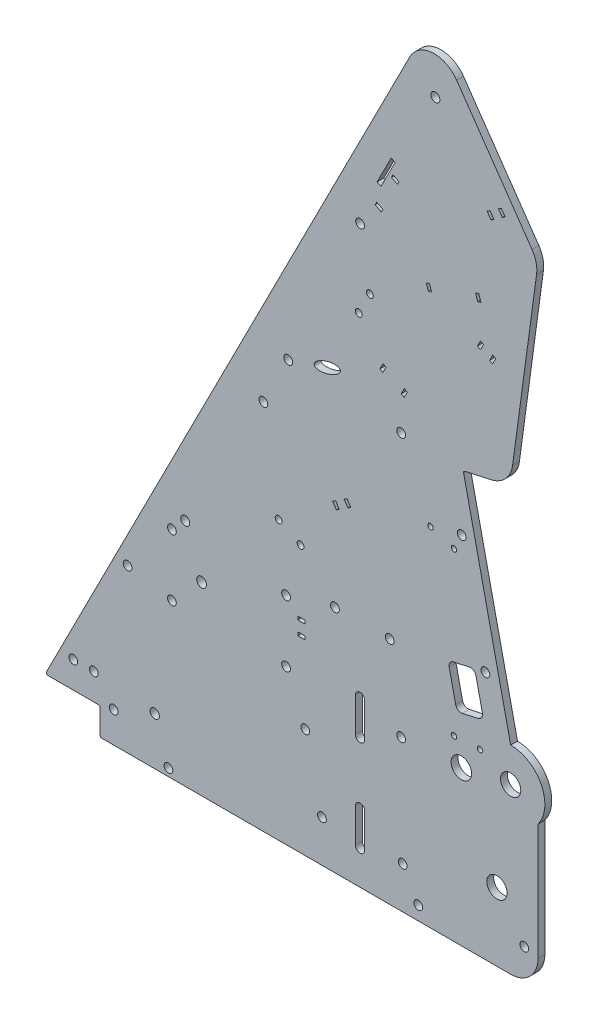
SolidWorks part; units mm, degrees
other "Markup1"
sketch "Sketch5"
ref_plane "Front Plane" through (0, 0, 0) normal (0, 0, 1) x (1, 0, 0)
ref_plane "Top Plane" through (0, 0, 0) normal (0, 1, 0) x (1, 0, 0)
ref_plane "Right Plane" through (0, 0, 0) normal (1, 0, 0) x (0, 0, -1)
sketch "Sketch1" plane through (0, 0, 0) normal (0, 0, 1) x (1, 0, 0)
  line L1 (228.6, -12.7) -> (228.6, 53.975)
  line L2 (178.7547, 351.4131) -> (0, 0)
  line L3 (228.6, 279.4) -> (178.7547, 351.4131)
  line L5 (0, 0) -> (25.4, 0)
  line L6 (25.4, 0) -> (25.4, -12.7)
  line L7 (25.4, -12.7) -> (228.6, -12.7)
  line L9 (215.9, 79.375) -> (193.9097, 178.5667)
  line L10 (193.9097, 178.5667) -> (215.6079, 183.377)
  line L11 (215.6079, 183.377) -> (228.6, 279.4)
  arc A0 (228.6, 53.975) -> (215.9, 79.375) centre (215.9, 63.5) ccw
  dimension "D7" = 12.7
  dimension "D8" = 76.2
  dimension "D10" = 31.75
  dimension "D2" = 292.1
  dimension "D3" = 25.4
  dimension "D4" = 215.9
  dimension "D5" = 394.2644
  dimension "D6" = 203.2
  dimension "D9" = 63.039
  dimension "D11" = 101.6
  dimension "D12" = 12.5
  dimension "D13" = 22.225
extrude "Boss-Extrude1" add sketch "Sketch1" along normal blind 3.175
sketch "Sketch2" plane through (0, 0, 3.175) normal (0, 0, 1) x (1, 0, 0)
  line L0 (178.7547, 351.4131) -> (0, 0) construction
  line L1 (25.4, -12.7) -> (228.6, -12.7) construction
  line L2 (215.9, 79.375) -> (193.9097, 178.5667) construction
  line L3 (193.9097, 178.5667) -> (215.6079, 183.377) construction
  line L4 (215.9, 79.375) -> (193.9097, 178.5667) construction
  line L5 (64.9432, 94.0578) -> (72.5445, 73.1732) construction
  line L6 (64.9432, 94.0578) -> (103.3734, 94.0578) construction
  line L10 (228.6, -12.7) -> (228.6, 53.975) construction
  circle A0 centre (64.9432, 94.0578) radius 2.0955
  circle A1 centre (180.975, 322.1643) radius 2.0955
  circle A2 centre (72.5445, 73.1732) radius 2.286
  circle A3 centre (193.2078, 152.3944) radius 2.032
  circle A4 centre (215.9, 63.5) radius 4.699
  circle A7 centre (173.0375, -6.35) radius 2.032
  circle A8 centre (204.203, 102.7985) radius 2.032
  circle A26 centre (209.55, 19.05) radius 4.699
  arc A30 (228.6, 53.975) -> (215.9, 79.375) centre (215.9, 63.5) ccw construction
  circle A31 centre (165.1, 179.3875) radius 2.032
  circle A35 centre (111.724, 87.4607) radius 2.032
  circle A36 centre (111.724, 58.8857) radius 2.032
  circle A37 centre (58.765, 58.8857) radius 2.032
  circle A38 centre (58.765, 87.4607) radius 2.032
  circle A39 centre (111.724, 58.8857) radius 1.905 construction
  circle A42 centre (111.724, 87.4607) radius 1.905 construction
  circle A43 centre (58.765, 58.8857) radius 1.905 construction
  circle A44 centre (58.765, 87.4607) radius 1.905 construction
  dimension "D3" = 4.191
  dimension "D5" = 4.191
  dimension "D9" = 4.572
  dimension "D20" = 9.398
  dimension "D23" = 9.398
  dimension "D18" = 4.064
  dimension "D26" = 4.064
  dimension "D14" = 4.064
  dimension "D10" = 4.064
  dimension "D2" = 15.24
  dimension "D6" = 15.24
  dimension "D7" = 22.225
  dimension "D21" = 44.45
  dimension "D22" = 6.35
  dimension "D19" = 160.3375
  dimension "D24" = 44.45
  dimension "D25" = 6.35
  dimension "D27" = 25.4
  dimension "D28" = 50.8
  dimension "D29" = 6.35
  dimension "D17" = 6.35
  dimension "D33" = 55.5625
  dimension "D15" = 114.3
  dimension "D4" = 180.975
  dimension "D8" = 70
extrude "Cut-Extrude1" cut sketch "Sketch2" against normal through all
sketch "Sketch7" plane through (0, 0, 3.175) normal (0, 0, 1) x (1, 0, 0)
  line L0 (146.05, 3.175) -> (146.05, 19.05) construction
  line L1 (143.891, 3.175) -> (143.891, 19.05)
  line L2 (148.209, 3.175) -> (148.209, 19.05)
  line L3 (146.05, 47.625) -> (146.05, 63.5) construction
  line L4 (143.891, 47.625) -> (143.891, 63.5)
  line L5 (148.209, 47.625) -> (148.209, 63.5)
  line L6 (25.4, -12.7) -> (228.6, -12.7) construction
  line L12 (228.6, -12.7) -> (228.6, 53.975) construction
  line L13 (25.4, -12.7) -> (228.6, -12.7) construction
  arc A0 (143.891, 3.175) -> (148.209, 3.175) centre (146.05, 3.175) ccw
  arc A1 (148.209, 19.05) -> (143.891, 19.05) centre (146.05, 19.05) ccw
  arc A2 (143.891, 47.625) -> (148.209, 47.625) centre (146.05, 47.625) ccw
  arc A3 (148.209, 63.5) -> (143.891, 63.5) centre (146.05, 63.5) ccw
  circle A8 centre (50.8, 9.525) radius 2.159
  point P2 (146.05, 11.1125)
  point P9 (146.05, 55.5625)
  dimension "D1" = 4.318
  dimension "D5" = 4.318
  dimension "D2" = 15.875
  dimension "D3" = 15.875
  dimension "D4" = 44.45
  dimension "D6" = 95.25
  dimension "D7" = 82.55
  dimension "D8" = 15.875
  dimension "D9" = 22.225
extrude "Cut-Extrude2" cut sketch "Sketch7" against normal through all
sketch "Sketch10" plane through (0, 0, 3.175) normal (0, 0, 1) x (1, 0, 0)
  circle A0 centre (120.65, 38.1) radius 2.032
  circle A1 centre (165.1, 57.15) radius 2.032
  circle A2 centre (13.0465, 12.3347) radius 2.032
  circle A3 centre (22.5715, 12.3347) radius 2.032
  circle A4 centre (38.2114, 62.6398) radius 2.032
  dimension "D1" = 4.064
  dimension "D3" = 38.1
  dimension "D2" = 120.65
  dimension "D4" = 63.5
  dimension "D5" = 69.85
extrude "Cut-Extrude3" cut sketch "Sketch10" against normal up to next
fillet "Fillet1" radius 12.7 4 edges at (228.6, -12.7, 1.5875) (178.7547, 351.4131, 1.5875) (215.6079, 183.377, 1.5875) (228.6, 279.4, 1.5875)
fillet "Fillet2" radius 0.7937 4 edges at (25.4, -12.7, 1.5875) (25.4, 0, 1.5875) (193.9097, 178.5667, 1.5875) (0, 0, 1.5875)
sketch "Sketch12" plane through (0, 0, 3.175) normal (0, 0, 1) x (1, 0, 0)
  circle A0 centre (31.75, 1.5875) radius 2.032
  circle A1 centre (173.0375, -6.35) radius 2.032
  circle A2 centre (222.25, 1.5875) radius 2.032
  circle A3 centre (57.15, -9.2075) radius 2.032
  circle A4 centre (57.15, -9.2075) radius 2.286 construction
  dimension "D1" = 4.064
  dimension "D2" = 4.064
extrude "Cut-Extrude5" cut sketch "Sketch12" against normal through all
sketch "Sketch13" plane through (0, 0, 3.175) normal (0, 0, 1) x (1, 0, 0)
  line L1 (228.6, 0) -> (228.6, 53.975) construction
  line L2 (1.2943, 0) -> (24.6062, 0) construction
  line L3 (26.1937, -12.7) -> (215.9, -12.7) construction
  line L8 (178.2697, 245.9923) -> (176.7582, 245.5069)
  line L9 (179.2404, 242.9693) -> (178.2697, 245.9923)
  line L10 (177.7289, 242.4839) -> (179.2404, 242.9693)
  line L11 (176.7582, 245.5069) -> (177.7289, 242.4839)
  line L12 (178.2697, 245.9923) -> (176.7582, 245.5069)
  line L13 (179.2404, 242.9693) -> (178.2697, 245.9923)
  line L14 (177.7289, 242.4839) -> (179.2404, 242.9693)
  line L15 (176.7582, 245.5069) -> (177.7289, 242.4839)
  line L16 (153.9381, 274.6148) -> (160.5022, 287.5193)
  line L17 (200.6096, 249.8308) -> (202.1211, 250.3161)
  line L18 (199.639, 252.8538) -> (200.6096, 249.8308)
  line L19 (201.1505, 253.3391) -> (199.639, 252.8538)
  line L20 (202.1211, 250.3161) -> (201.1505, 253.3391)
  line L21 (200.6096, 249.8308) -> (202.1211, 250.3161)
  line L22 (199.639, 252.8538) -> (200.6096, 249.8308)
  line L23 (201.1505, 253.3391) -> (199.639, 252.8538)
  line L24 (202.1211, 250.3161) -> (201.1505, 253.3391)
  line L25 (153.9381, 274.6148) -> (155.7207, 273.708)
  line L26 (160.5905, 279.7801) -> (163.4204, 278.3406)
  line L27 (161.3102, 281.1951) -> (160.5905, 279.7801)
  line L28 (164.1402, 279.7556) -> (161.3102, 281.1951)
  line L29 (163.4204, 278.3406) -> (164.1402, 279.7556)
  line L30 (160.5905, 279.7801) -> (163.4204, 278.3406)
  line L31 (161.3102, 281.1951) -> (160.5905, 279.7801)
  line L32 (164.1402, 279.7556) -> (161.3102, 281.1951)
  line L33 (163.4204, 278.3406) -> (164.1402, 279.7556)
  line L34 (160.5022, 287.5193) -> (162.2849, 286.6125)
  line L35 (155.7207, 273.708) -> (162.2849, 286.6125)
  line L36 (153.7897, 266.4104) -> (153.0699, 264.9954)
  line L37 (156.6196, 264.9709) -> (153.7897, 266.4104)
  line L38 (155.8998, 263.5559) -> (156.6196, 264.9709)
  line L39 (153.0699, 264.9954) -> (155.8998, 263.5559)
  line L40 (153.7897, 266.4104) -> (153.0699, 264.9954)
  line L41 (156.6196, 264.9709) -> (153.7897, 266.4104)
  line L42 (155.8998, 263.5559) -> (156.6196, 264.9709)
  line L43 (153.0699, 264.9954) -> (155.8998, 263.5559)
  line L110 (153.9925, 274.7218) -> (157.3929, 281.4066) construction
  line L111 (155.7751, 273.815) -> (159.1755, 280.4999) construction
  line L122 (203.3303, 234.0299) -> (201.9154, 234.7497)
  line L123 (201.8908, 231.2) -> (203.3303, 234.0299)
  line L124 (200.4759, 231.9198) -> (201.8908, 231.2)
  line L125 (201.9154, 234.7497) -> (200.4759, 231.9198)
  line L126 (203.3303, 234.0299) -> (201.9154, 234.7497)
  line L127 (201.8908, 231.2) -> (203.3303, 234.0299)
  line L128 (200.4759, 231.9198) -> (201.8908, 231.2)
  line L129 (201.9154, 234.7497) -> (200.4759, 231.9198)
  line L130 (206.1357, 229.0407) -> (207.5507, 228.321)
  line L131 (207.5752, 231.8707) -> (206.1357, 229.0407)
  line L132 (208.9902, 231.1509) -> (207.5752, 231.8707)
  line L133 (207.5507, 228.321) -> (208.9902, 231.1509)
  line L134 (206.1357, 229.0407) -> (207.5507, 228.321)
  line L135 (207.5752, 231.8707) -> (206.1357, 229.0407)
  line L136 (208.9902, 231.1509) -> (207.5752, 231.8707)
  line L137 (207.5507, 228.321) -> (208.9902, 231.1509)
  line L138 (211.5405, 292.889) -> (210.2352, 291.9855)
  line L139 (213.3475, 290.2784) -> (211.5405, 292.889)
  line L140 (212.0422, 289.3749) -> (213.3475, 290.2784)
  line L141 (210.2352, 291.9855) -> (212.0422, 289.3749)
  line L142 (211.5405, 292.889) -> (210.2352, 291.9855)
  line L143 (213.3475, 290.2784) -> (211.5405, 292.889)
  line L144 (212.0422, 289.3749) -> (213.3475, 290.2784)
  line L145 (210.2352, 291.9855) -> (212.0422, 289.3749)
  line L146 (206.3193, 289.275) -> (205.014, 288.3715)
  line L147 (208.1263, 286.6644) -> (206.3193, 289.275)
  line L148 (206.821, 285.7609) -> (208.1263, 286.6644)
  line L149 (205.014, 288.3715) -> (206.821, 285.7609)
  line L150 (206.3193, 289.275) -> (205.014, 288.3715)
  line L151 (208.1263, 286.6644) -> (206.3193, 289.275)
  line L152 (206.821, 285.7609) -> (208.1263, 286.6644)
  line L153 (205.014, 288.3715) -> (206.821, 285.7609)
  line L184 (133.3504, 136.102) -> (135.0815, 133.4404)
  line L185 (133.3504, 136.102) -> (134.6812, 136.9675)
  line L186 (135.0815, 133.4404) -> (136.4123, 134.3059)
  line L187 (155.2281, 200.1197) -> (156.643, 199.3999)
  line L188 (156.6676, 202.9496) -> (155.2281, 200.1197)
  line L189 (158.0826, 202.2298) -> (156.6676, 202.9496)
  line L190 (156.643, 199.3999) -> (158.0826, 202.2298)
  line L191 (155.2281, 200.1197) -> (156.643, 199.3999)
  line L192 (156.6676, 202.9496) -> (155.2281, 200.1197)
  line L193 (158.0826, 202.2298) -> (156.6676, 202.9496)
  line L194 (156.643, 199.3999) -> (158.0826, 202.2298)
  line L195 (134.6812, 136.9675) -> (136.4123, 134.3059)
  line L196 (165.1328, 195.0814) -> (166.5478, 194.3617)
  line L197 (166.5723, 197.9113) -> (165.1328, 195.0814)
  line L198 (167.9873, 197.1916) -> (166.5723, 197.9113)
  line L199 (166.5478, 194.3617) -> (167.9873, 197.1916)
  line L200 (165.1328, 195.0814) -> (166.5478, 194.3617)
  line L201 (166.5723, 197.9113) -> (165.1328, 195.0814)
  line L202 (167.9873, 197.1916) -> (166.5723, 197.9113)
  line L203 (166.5478, 194.3617) -> (167.9873, 197.1916)
  line L204 (140.4047, 136.9025) -> (138.6737, 139.5641)
  line L205 (140.4047, 136.9025) -> (141.7355, 137.768)
  line L206 (138.6737, 139.5641) -> (140.0045, 140.4296)
  line L207 (141.7355, 137.768) -> (140.0045, 140.4296)
  line L209 (169.1053, 332.4434) -> (0.5868, 1.1536) construction
  line L210 (88.0466, 102.1523) -> (85.2167, 103.5918) construction
  line L288 (117.2485, 81.8727) -> (120.4235, 81.8727)
  line L289 (117.2485, 81.8727) -> (117.2485, 80.2852)
  line L290 (120.4235, 81.8727) -> (120.4235, 80.2852)
  line L291 (117.2485, 80.2852) -> (120.4235, 80.2852)
  line L292 (117.2485, 75.5227) -> (120.4235, 75.5227)
  line L293 (117.2485, 75.5227) -> (117.2485, 73.9352)
  line L294 (120.4235, 75.5227) -> (120.4235, 73.9352)
  line L295 (117.2485, 73.9352) -> (120.4235, 73.9352)
  line L297 (115.661, 86.2542) -> (115.661, 60.0922) construction
  line L298 (59.9715, 91.3977) -> (110.5175, 91.3977) construction
  circle A0 centre (112.7125, 182.5625) radius 2.032
  circle A1 centre (146.05, 254) radius 2.032
  circle A2 centre (101.1964, 159.9231) radius 2.032 construction
  circle A3 centre (101.1964, 159.9231) radius 2.032
  circle A4 centre (145.4254, 217.7376) radius 1.6 construction
  circle A5 centre (150.594, 227.8985) radius 1.6 construction
  circle A7 centre (145.4254, 217.7376) radius 1.6
  circle A8 centre (150.594, 227.8985) radius 1.6
  circle A9 centre (108.294, 116.1502) radius 1.6 construction
  circle A10 centre (118.455, 110.9816) radius 1.6 construction
  circle A11 centre (108.294, 116.1502) radius 1.6
  circle A12 centre (118.455, 110.9816) radius 1.6
  ellipse E0 centre (130.8261, 188.4615) end of major axis (136.864, 190.4279) minor radius 2.3812 construction
  ellipse E1 centre (130.8261, 188.4615) end of major axis (136.864, 190.4279) minor radius 2.3812
  point P44 (134.7747, 137.6284)
  dimension "D2" = 4.064
  dimension "D5" = 4.064
  dimension "D1" = 195.2625
  dimension "D3" = 82.55
  dimension "D4" = 254
  dimension "D6" = 115.8875
  dimension "D11" = 7.62
  dimension "D12" = 6.858
  dimension "D13" = 1.5875
  dimension "D14" = 3.175
  dimension "D15" = 4.7625
  dimension "D16" = 60
  dimension "D17" = 57.15
  dimension "D24" = 50.8
  dimension "D29" = 3.175
  dimension "D30" = 1.5875
  dimension "D31" = 4.7625
  dimension "D32" = 1.5875
  dimension "D33" = 9.525
  dimension "D7" = 0
  dimension "D8" = 0
  dimension "D9" = 0
  dimension "D10" = 0
  dimension "D18" = 0
  dimension "D19" = 0
  dimension "D20" = 0
  dimension "D21" = 0
  dimension "D22" = 0
  dimension "D23" = 0
extrude "Cut-Extrude6" cut sketch "Sketch13" against normal through all
sketch "Sketch14" plane through (0, 0, 3.175) normal (0, 0, 1) x (1, 0, 0)
  line L5 (186.8444, 98.9502) -> (199.2434, 101.699)
  line L6 (186.8444, 98.9502) -> (190.9676, 80.3518)
  line L7 (190.9676, 80.3518) -> (203.3665, 83.1006)
  line L8 (199.2434, 101.699) -> (203.3665, 83.1006)
  line L14 (202.8168, 85.5804) -> (199.7931, 99.2192) construction
  line L15 (193.4474, 80.9015) -> (200.8868, 82.5508) construction
  line L16 (187.3942, 96.4704) -> (190.4178, 82.8316) construction
  line L17 (196.7636, 101.1493) -> (189.3242, 99.5) construction
  circle A0 centre (189.6022, 69.9806) radius 1.27
  circle A1 centre (201.7089, 70.5092) radius 1.27
  circle A2 centre (189.6022, 69.9806) radius 1.27 construction
  circle A3 centre (201.7089, 70.5092) radius 1.27 construction
  circle A4 centre (159.7935, 93.98) radius 2.032
  circle A5 centre (134.3935, 93.98) radius 2.032
  circle A6 centre (178.7216, 148.5324) radius 1.27
  circle A8 centre (178.7216, 148.5324) radius 1.27 construction
  circle A9 centre (189.6226, 145.0954) radius 1.27
  circle A10 centre (189.6226, 145.0954) radius 1.27 construction
  circle A11 centre (128.361, 6.6675) radius 2.032
  circle A12 centre (165.826, 6.6675) radius 2.032
  point P8 (152.4, 88.9)
  point P46 (195.1622, 128.7736)
  point P47 (195.1435, 116.5414)
  dimension "D1" = 4.064
extrude "Cut-Extrude7" cut sketch "Sketch14" against normal through all both and the other way through all
fillet "Fillet3" radius 2.54 4 edges at (199.2434, 101.699, 1.5875) (186.8444, 98.9502, 1.5875) (190.9676, 80.3518, 1.5875) (203.3665, 83.1006, 1.5875)
sketch "Sketch15" plane through (0, 0, 3.175) normal (0, 0, 1) x (1, 0, 0)
  circle A0 centre (193.04, 58.801) radius 4.7625 construction
  circle A1 centre (193.04, 58.801) radius 4.7625
extrude "Cut-Extrude8" cut sketch "Sketch15" against normal through all
equation "\"D6@Sketch2\"=\"D2@Sketch2\""
